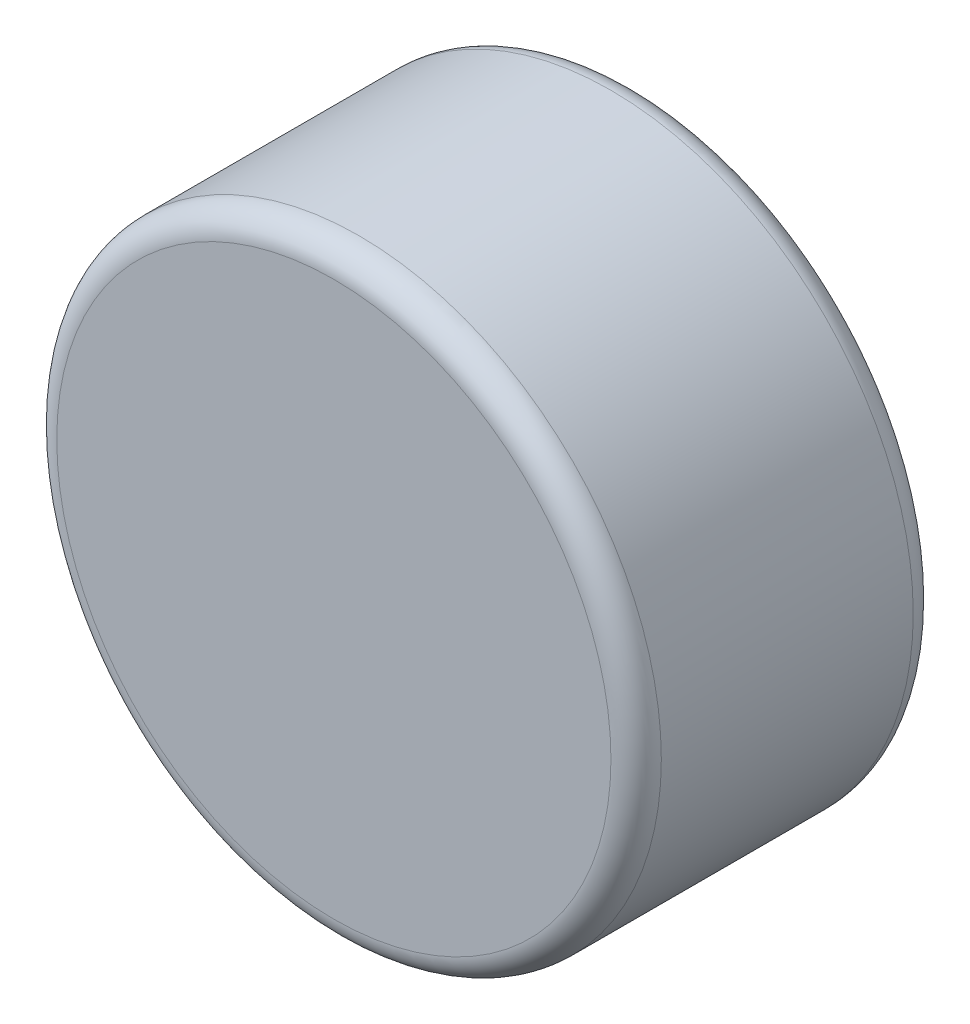
SolidWorks part; units mm, degrees
material "Stainless Steel (ferritic)"
ref_plane "Top Plane" through (0, 0, 0) normal (0, 0, 1) x (1, 0, 0)
ref_plane "Front Plane" through (0, 0, 0) normal (0, 1, 0) x (1, 0, 0)
ref_plane "Right Plane" through (0, 0, 0) normal (1, 0, 0) x (0, 0, -1)
sketch "Sketch1" plane through (0, 0, 0) normal (0, 0, 1) x (1, 0, 0)
  circle A0 centre (0, 0) radius 3
  dimension "D1" = 6
extrude "Boss-Extrude1" add sketch "Sketch1" along normal blind 3
fillet "Fillet1" radius 0.25 2 edges at (3, 0, 0) (3, 0, 3)
